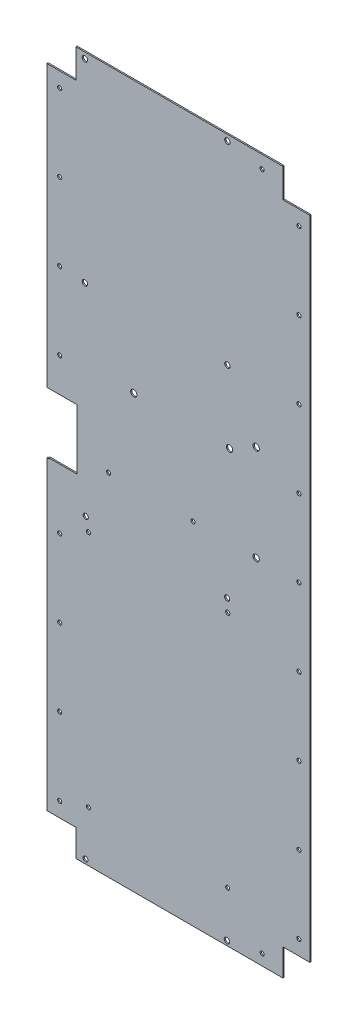
SolidWorks part; units mm, degrees
material "Nikiel"
ref_plane "Front" through (0, 0, 0) normal (0, 0, 1) x (1, 0, 0)
ref_plane "Top" through (0, 0, 0) normal (0, 1, 0) x (1, 0, 0)
ref_plane "Right" through (0, 0, 0) normal (1, 0, 0) x (0, 0, -1)
sketch "Szkic1" plane through (0, 0, 0) normal (0, 0, 1) x (1, 0, 0)
  line L1 (-116.4886, 124.774) -> (86.5114, 124.774)
  line L2 (-116.4886, 124.774) -> (-116.4886, -420.226)
  line L3 (-116.4886, -420.226) -> (86.5114, -420.226)
  line L4 (86.5114, 124.774) -> (86.5114, -420.226)
  dimension "D1" = 203
  dimension "D2" = 545
extrude "Dodanie-wyciągnięcie1" add sketch "Szkic1" along normal blind 1
sketch "Szkic2" plane through (0, 0, 1) normal (0, 0, 1) x (1, 0, 0)
  line L1 (-116.4886, 124.774) -> (-95.4886, 124.774)
  line L2 (-116.4886, 124.774) -> (-116.4886, 103.774)
  line L3 (-116.4886, 103.774) -> (-95.4886, 103.774)
  line L4 (-95.4886, 124.774) -> (-95.4886, 103.774)
  line L5 (86.5114, 124.774) -> (65.5114, 124.774)
  line L6 (86.5114, 124.774) -> (86.5114, 103.774)
  line L7 (86.5114, 103.774) -> (65.5114, 103.774)
  line L8 (65.5114, 124.774) -> (65.5114, 103.774)
  dimension "D1" = 21
  dimension "D2" = 21
  dimension "D3" = 21
  dimension "D4" = 21
extrude "Wytnij-wyciągnięcie1" cut sketch "Szkic2" against normal through all both and the other way through all
sketch "Szkic3" plane through (0, 0, 1) normal (0, 0, 1) x (1, 0, 0)
  line L1 (86.5114, -420.226) -> (65.5114, -420.226)
  line L2 (86.5114, -420.226) -> (86.5114, -399.226)
  line L3 (86.5114, -399.226) -> (65.5114, -399.226)
  line L4 (65.5114, -420.226) -> (65.5114, -399.226)
  line L5 (-116.4886, -420.226) -> (-95.4886, -420.226)
  line L6 (-116.4886, -420.226) -> (-116.4886, -399.226)
  line L7 (-116.4886, -399.226) -> (-95.4886, -399.226)
  line L8 (-95.4886, -420.226) -> (-95.4886, -399.226)
  dimension "D1" = 21
  dimension "D2" = 21
  dimension "D3" = 21
  dimension "D4" = 21
extrude "Wytnij-wyciągnięcie2" cut sketch "Szkic3" against normal through all
sketch "Szkic4" plane through (0, 0, 1) normal (0, 0, 1) x (1, 0, 0)
  line L0 (-116.4886, -138.8995) -> (-116.4886, -136.8995) construction
  line L1 (-116.4886, 103.774) -> (-116.4886, -399.226) construction
  line L2 (-116.4886, -157.9633) -> (-116.4886, -160.9633) construction
  line L8 (-116.4886, -160.9633) -> (-94.4886, -160.9633)
  line L9 (-116.4886, -160.9633) -> (-116.4886, -114.2414)
  line L10 (-116.4886, -114.2414) -> (-94.4886, -114.2414)
  line L11 (-94.4886, -160.9633) -> (-94.4886, -114.2414)
  dimension "D1" = 2
  dimension "D2" = 3
  dimension "D3" = 22
extrude "Wytnij-wyciągnięcie3" cut sketch "Szkic4" against normal through all
sketch "Szkic5" plane through (0, 124.774, 0) normal (0, 1, 0) x (1, 0, 0)
  line L1 (65.5114, 0) -> (-95.4886, 0)
  line L2 (65.5114, 0) -> (65.5114, -1)
  line L3 (65.5114, -1) -> (-95.4886, -1)
  line L4 (-95.4886, 0) -> (-95.4886, -1)
extrude "Dodanie-wyciągnięcie2" add sketch "Szkic5" along normal blind 1.5
sketch "Szkic6" plane through (0, 0, 1) normal (0, 0, 1) x (1, 0, 0)
  circle A0 centre (22.4114, -29.126) radius 2.1
  circle A1 centre (22.4114, 121.674) radius 2.1
  circle A2 centre (-88.3886, 121.674) radius 2.1
  circle A3 centre (-88.3886, -29.126) radius 2.1
extrude "Wytnij-wyciągnięcie4" cut sketch "Szkic6" against normal through all
sketch "Szkic7" plane through (0, 0, 1) normal (0, 0, 1) x (1, 0, 0)
  circle A0 centre (-50.4386, -84.4645) radius 2.45
  circle A1 centre (24.0614, -84.4645) radius 2.45
  circle A2 centre (44.7728, -73.226) radius 2.45
  circle A3 centre (44.7728, -147.726) radius 2.45
extrude "Wytnij-wyciągnięcie5" cut sketch "Szkic7" against normal through all
sketch "Szkic8" plane through (-116.4886, 0, 0) normal (-1, 0, 0) x (0, 0, 1)
  line L1 (0, -114.2414) -> (1, -114.2414)
  line L2 (0, -114.2414) -> (0, 103.774)
  line L3 (0, 103.774) -> (1, 103.774)
  line L4 (1, -114.2414) -> (1, 103.774)
extrude "Dodanie-wyciągnięcie3" add sketch "Szkic8" along normal up to surface (1.5 mm away)
sketch "Szkic9" plane through (-116.4886, 0, 0) normal (-1, 0, 0) x (0, 0, 1)
  line L0 (1, -160.9633) -> (1, -399.226) construction
  line L1 (0, -399.226) -> (1, -399.226)
  line L2 (0, -399.226) -> (0, -161.6955)
  line L3 (0, -161.6955) -> (1, -161.6955)
  line L4 (1, -399.226) -> (1, -161.6955)
extrude "Dodanie-wyciągnięcie4" add sketch "Szkic9" along normal up to surface (1.5 mm away)
sketch "Szkic10" plane through (0, 0, 1) normal (0, 0, 1) x (1, 0, 0)
  line L0 (-87.8886, -413.5413) -> (-87.8886, -419.0283) construction
  line L2 (-86.968, -413.5413) -> (-88.8092, -413.5413) construction
  line L3 (-89.7886, -416.7913) -> (-85.9886, -416.7913) construction
  line L4 (-89.7886, -414.5208) -> (-89.7886, -419.0619) construction
  line L5 (-85.9886, -419.0619) -> (-85.9886, -414.5208) construction
  circle A0 centre (22.2114, -186.0413) radius 2
  circle A1 centre (22.6625, -195.6924) radius 1.6511
  circle A2 centre (-87.7386, -186.0413) radius 2
  circle A3 centre (-85.5886, -195.6413) radius 1.6
  circle A4 centre (-85.5886, -380.9413) radius 1.6
  circle A5 centre (22.6114, -380.9413) radius 1.6
  circle A6 centre (22.0114, -416.7913) radius 2.1
  circle A7 centre (-87.8886, -416.7913) radius 1.9
extrude "Wytnij-wyciągnięcie6" cut sketch "Szkic10" against normal through all
sketch "Szkic11" plane through (0, 0, 0) normal (0, 0, -1) x (-1, 0, 0)
  line L0 (4.3253, -147.726) -> (94.956, -147.726) construction
  line L1 (-78.0114, -162.2672) -> (-78.0114, -113.5927) construction
  line L2 (4.3253, -147.726) -> (-86.5114, -147.726) construction
  line L3 (-86.5114, -399.226) -> (-86.5114, 103.774) construction
  line L4 (-86.5114, -399.226) -> (-86.5114, 103.774) construction
  circle A0 centre (4.3253, -147.726) radius 1.6
  circle A1 centre (69.9875, -147.726) radius 1.6
  circle A2 centre (-78.0114, -147.726) radius 1.6
  dimension "D1" = 8.5
extrude "Wytnij-wyciągnięcie7" cut sketch "Szkic11" against normal through all
sketch "Szkic12" plane through (0, 0, 1) normal (0, 0, 1) x (1, 0, 0)
  line L0 (-107.9886, -399.226) -> (-107.9886, 103.774) construction
  line L1 (-117.9886, -399.226) -> (-117.9886, -161.6955) construction
  line L2 (-95.4886, -399.226) -> (-187.6359, -399.226) construction
  line L3 (-95.4886, 103.774) -> (-195.7623, 103.774) construction
  line L4 (-107.9886, -147.726) -> (-207.1733, -147.726) construction
  line L5 (78.0114, -467.5484) -> (78.0114, 135.0585) construction
  line L6 (86.5114, -399.226) -> (86.5114, 103.774) construction
  line L7 (-107.9886, -387.726) -> (95.3402, -387.726) construction
  line L8 (-107.9886, -327.726) -> (164.5544, -327.726) construction
  line L9 (-107.9886, -267.726) -> (145.2804, -267.726) construction
  line L10 (-107.9886, -207.726) -> (176.0489, -207.726) construction
  line L11 (-107.9886, -87.726) -> (155.3643, -87.726) construction
  line L12 (-107.9886, -27.726) -> (164.5544, -27.726) construction
  line L13 (-107.9886, 32.274) -> (155.3643, 32.274) construction
  line L14 (-107.9886, 92.274) -> (169.2987, 92.274) construction
  line L15 (-95.4886, 116.274) -> (65.5114, 116.274) construction
  line L16 (65.5114, 126.274) -> (-95.4886, 126.274) construction
  line L17 (-95.4886, 116.274) -> (-95.4886, 174.3207) construction
  line L18 (65.5114, 115.024) -> (65.5114, 190.7177) construction
  line L19 (65.5114, 126.274) -> (65.5114, 103.774) construction
  line L20 (49.4053, 116.274) -> (49.4053, -521.3087) construction
  line L21 (12.2459, -411.726) -> (112.4593, -411.726) construction
  line L22 (-95.4886, -420.226) -> (65.5114, -420.226) construction
  circle A0 centre (-107.9886, -87.726) radius 1.6
  circle A1 centre (-107.9886, -27.726) radius 1.6
  circle A2 centre (-107.9886, 32.274) radius 1.6
  circle A3 centre (-107.9886, 92.274) radius 1.6
  circle A4 centre (-107.9886, -207.726) radius 1.6
  circle A5 centre (-107.9886, -267.726) radius 1.6
  circle A6 centre (-107.9886, -327.726) radius 1.6
  circle A7 centre (-107.9886, -387.726) radius 1.6
  circle A8 centre (78.0114, 92.274) radius 1.6
  circle A9 centre (78.0114, 32.274) radius 1.6
  circle A10 centre (78.0114, -27.726) radius 1.6
  circle A11 centre (78.0114, -87.726) radius 1.6
  circle A12 centre (78.0114, -207.726) radius 1.6
  circle A13 centre (78.0114, -267.726) radius 1.6
  circle A14 centre (78.0114, -327.726) radius 1.6
  circle A15 centre (78.0114, -387.726) radius 1.6
  circle A16 centre (49.4053, 116.274) radius 1.6
  circle A17 centre (49.4053, -411.726) radius 1.6
  dimension "D2" = 60
  dimension "D3" = 60
  dimension "D4" = 60
  dimension "D5" = 60
  dimension "D6" = 60
  dimension "D7" = 60
  dimension "D8" = 60
  dimension "D9" = 60
  dimension "D11" = 10
  dimension "D12" = 8.5
  dimension "D1" = 10
  dimension "D10" = 8.5
extrude "Wytnij-wyciągnięcie8" cut sketch "Szkic12" against normal through all
